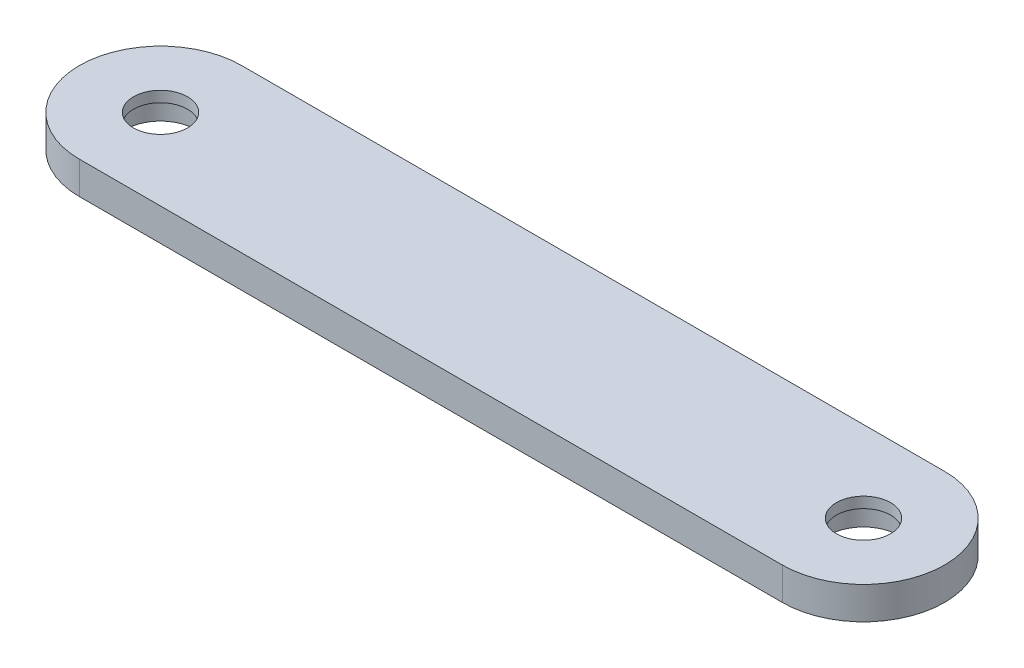
SolidWorks part; units mm, degrees
ref_plane "Front Plane" through (0, 0, 0) normal (0, 0, 1) x (1, 0, 0)
ref_plane "Top Plane" through (0, 0, 0) normal (0, 1, 0) x (1, 0, 0)
ref_plane "Right Plane" through (0, 0, 0) normal (1, 0, 0) x (0, 0, -1)
sketch "Sketch2" plane through (0, 0, 0) normal (0, 1, 0) x (1, 0, 0)
  line L1 (-6.5, 28.5) -> (123.5, 28.5)
  line L3 (-6.5, -1.5) -> (123.5, -1.5)
  arc A0 (-6.5, 28.5) -> (-6.5, -1.5) centre (-6.5, 13.5) ccw
  circle A1 centre (-6.5, 13.5) radius 5
  arc A2 (123.5, -1.5) -> (123.5, 28.5) centre (123.5, 13.5) ccw
  circle A3 centre (123.5, 13.5) radius 5
  point P0 (0, 0)
  point P9 (0, 0)
extrude "Boss-Extrude1" add sketch "Sketch2" along normal blind 6
sketch "Sketch4" plane through (0, 0, 0) normal (0, -1, 0) x (1, 0, 0)
  circle A0 centre (123.5, -13.5) radius 6.5
  circle A1 centre (-6.5, -13.5) radius 6.5
extrude "Cut-Extrude1" cut sketch "Sketch4" against normal blind 4
